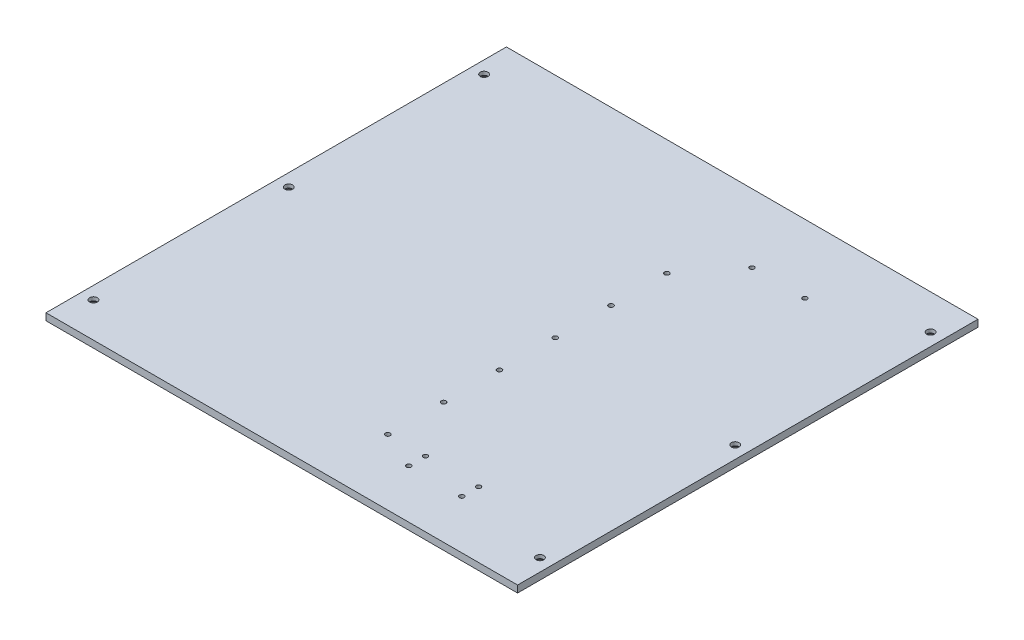
SolidWorks part; units mm, degrees
material "6061-O (SS)"
ref_plane "정면" through (0, 0, 0) normal (0, 0, 1) x (1, 0, 0)
ref_plane "윗면" through (0, 0, 0) normal (0, 1, 0) x (1, 0, 0)
ref_plane "우측면" through (0, 0, 0) normal (1, 0, 0) x (0, 0, -1)
sketch "스케치1" plane through (0, 0, 0) normal (0, 1, 0) x (1, 0, 0)
  line L1 (0, 0) -> (340, 0)
  line L2 (0, 0) -> (0, 330)
  line L3 (0, 330) -> (340, 330)
  line L4 (340, 0) -> (340, 330)
  dimension "D1" = 330
  dimension "D2" = 340
extrude "보스-돌출1" add sketch "스케치1" along normal blind 5
hole_wizard "M4x0.7 나사 구멍2" positions "스케치3" profile "스케치2" tap size "M4x0.7" standard "Ansi Metric"
sketch "스케치3" plane through (0, 5, 0) normal (0, 1, 0) x (1, 0, 0)
  line L0 (226, 281) -> (264, 281) construction
  line L1 (264, 281) -> (264, 35) construction
  line L2 (264, 35) -> (226, 35) construction
  line L3 (226, 35) -> (226, 281) construction
  line L4 (264, 47) -> (226, 47) construction
  line L5 (0, 0) -> (340, 0) construction
  line L6 (340, 0) -> (340, 330) construction
  point P1 (226, 281)
  point P2 (264, 281)
  point P3 (264, 35)
  point P5 (226, 35)
  point P6 (264, 47)
  point P7 (226, 47)
  dimension "D1" = 12
  dimension "D2" = 38
  dimension "D3" = 234
  dimension "D4" = 35
  dimension "D5" = 76
sketch "스케치2" plane through (226, 5, -281) normal (1, 0, 0) x (0, 0, 1)
  line L0 (0, 0) -> (0, 12.4914)
  line L1 (0, 12.4914) -> (1.65, 11.5)
  line L2 (1.65, 11.5) -> (1.65, 0)
  line L5 (1.65, 0) -> (0, 0)
  line L10 (0, 12.4914) -> (-1.65, 11.5) construction
  line L11 (0, -6.35) -> (0, 107.95) construction
  dimension "탭 드릴 지름" = 3.3
  dimension "탭 드릴 깊이" = 11.5
  dimension "드릴 각도" = 118
cosmetic thread "구멍 나사산1" parameters "D1"=5, "D2"=4
cosmetic thread "구멍 나사산2" parameters "D1"=5, "D2"=4
cosmetic thread "구멍 나사산3" parameters "D1"=5, "D2"=4
cosmetic thread "구멍 나사산4" parameters "D1"=5, "D2"=4
cosmetic thread "구멍 나사산5" parameters "D1"=5, "D2"=4
cosmetic thread "구멍 나사산6" parameters "D1"=5, "D2"=4
sketch "스케치4" plane through (0, 5, 0) normal (0, 1, 0) x (1, 0, 0)
  line L0 (340, 330) -> (0, 330) construction
  line L1 (339, 330) -> (340, 330)
  line L2 (339, 330) -> (339, 0)
  line L3 (339, 0) -> (340, 0)
  line L4 (340, 330) -> (340, 0)
  line L6 (1, 330) -> (0, 330)
  line L7 (1, 330) -> (1, 0)
  line L8 (1, 0) -> (0, 0)
  line L9 (0, 330) -> (0, 0)
  dimension "D1" = 1
  dimension "D2" = 1
extrude "컷-돌출1" cut sketch "스케치4" against normal blind 10
hole_wizard "M3 여유 구멍1" positions "스케치6" profile "스케치5" hole size "M3" standard "Ansi Metric"
sketch "스케치6" plane through (0, 0, 0) normal (0, -1, 0) x (-1, 0, 0)
  line L0 (-199, 47) -> (-199, 87) construction
  line L1 (-199, 87) -> (-199, 127) construction
  line L2 (-199, 127) -> (-199, 167) construction
  line L3 (-199, 167) -> (-199, 207) construction
  line L4 (-199, 207) -> (-199, 247) construction
  line L5 (-1, 0) -> (-339, 0) construction
  circle A0 centre (-226, 47) radius 1.65 construction
  point P1 (-199, 47)
  point P2 (-199, 87)
  point P4 (-199, 127)
  point P6 (-199, 167)
  point P8 (-199, 207)
  point P10 (-199, 247)
  dimension "D2" = 27
  dimension "D1" = 47
  dimension "D3" = 40
sketch "스케치5" plane through (199, 0, -47) normal (1, 0, 0) x (0, 0, -1)
  line L0 (0, 0) -> (0, 21.0215)
  line L1 (0, 21.0215) -> (1.7, 20)
  line L2 (1.7, 20) -> (1.7, 0)
  line L5 (1.7, 0) -> (0, 0)
  line L10 (0, 21.0215) -> (-1.7, 20) construction
  line L11 (0, -6.35) -> (0, 107.95) construction
  dimension "구멍 지름" = 3.4
  dimension "구멍 깊이" = 20
  dimension "드릴 각도" = 118
hole_wizard "M5 납작 머리 작은 나사용 카운터싱크1" positions "스케치9" profile "스케치7" countersink size "M5" standard "Ansi Metric" end condition through all
sketch "스케치9" plane through (0, 0, 0) normal (0, -1, 0) x (-1, 0, 0)
  line L0 (-330, 25) -> (-10, 25) construction
  line L1 (-10, 25) -> (-10, 165) construction
  line L2 (-10, 165) -> (-10, 305) construction
  line L3 (-10, 305) -> (-330, 305) construction
  line L4 (-330, 305) -> (-330, 165) construction
  line L5 (-330, 165) -> (-330, 25) construction
  line L8 (-10, 165) -> (-330, 165) construction
  line L11 (-339, 165) -> (-330, 165) construction
  line L12 (-339, 0) -> (-339, 330) construction
  line L17 (-10, 165) -> (-1, 165) construction
  line L18 (-1, 330) -> (-1, 0) construction
  point P0 (-10, 25)
  point P2 (-10, 165)
  point P4 (-10, 305)
  point P6 (-330, 305)
  point P8 (-330, 165)
  point P10 (-330, 25)
  dimension "D1" = 320
  dimension "D2" = 140
sketch "스케치7" plane through (10, 0, -25) normal (1, 0, 0) x (0, 0, -1)
  line L0 (0, 0) -> (0, 5)
  line L1 (0, 5) -> (2.75, 5)
  line L2 (2.75, 5) -> (2.75, 2.45)
  line L3 (2.75, 2.45) -> (5.2, 0)
  line L5 (5.2, 0) -> (0, 0)
  line L6 (-2.75, 2.45) -> (-5.2, 0) construction
  line L11 (0, -6.35) -> (0, 107.95) construction
  dimension "관통 구멍 지름" = 5.5
  dimension "관통 구멍 깊이" = 5
  dimension "표면 카운터싱크 지름" = 10.4
  dimension "표면 카운터싱크 각도" = 90
